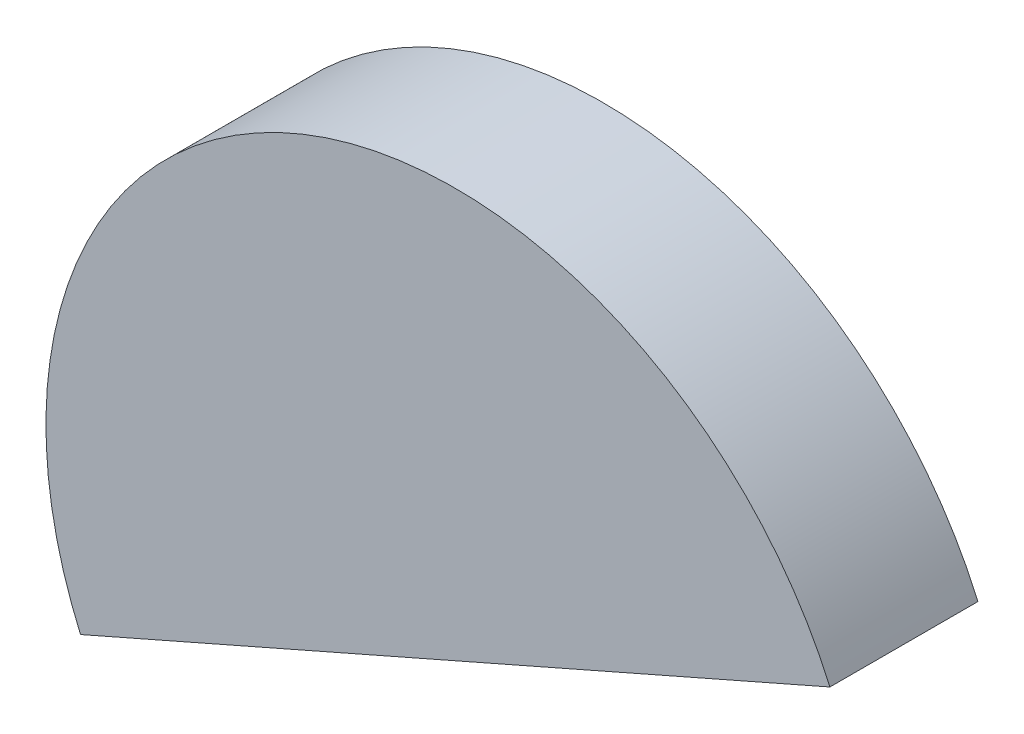
SolidWorks part; units mm, degrees
ref_plane "Front Plane" through (0, 0, 0) normal (0, 0, 1) x (1, 0, 0)
ref_plane "Top Plane" through (0, 0, 0) normal (0, 1, 0) x (1, 0, 0)
ref_plane "Right Plane" through (0, 0, 0) normal (1, 0, 0) x (0, 0, -1)
sketch "CurveSketch" plane through (0, 0, 0) normal (0, 0, 1) x (1, 0, 0)
  line L0 (-23.2013, 5.7822) -> (12.9273, 21.6558)
  arc A0 (12.9273, 21.6558) -> (-23.2013, 5.7822) centre (-5.137, 13.719) ccw
  dimension "D1" = 19.731
extrude "CurveBoss" add sketch "CurveSketch" along normal blind 7.139
